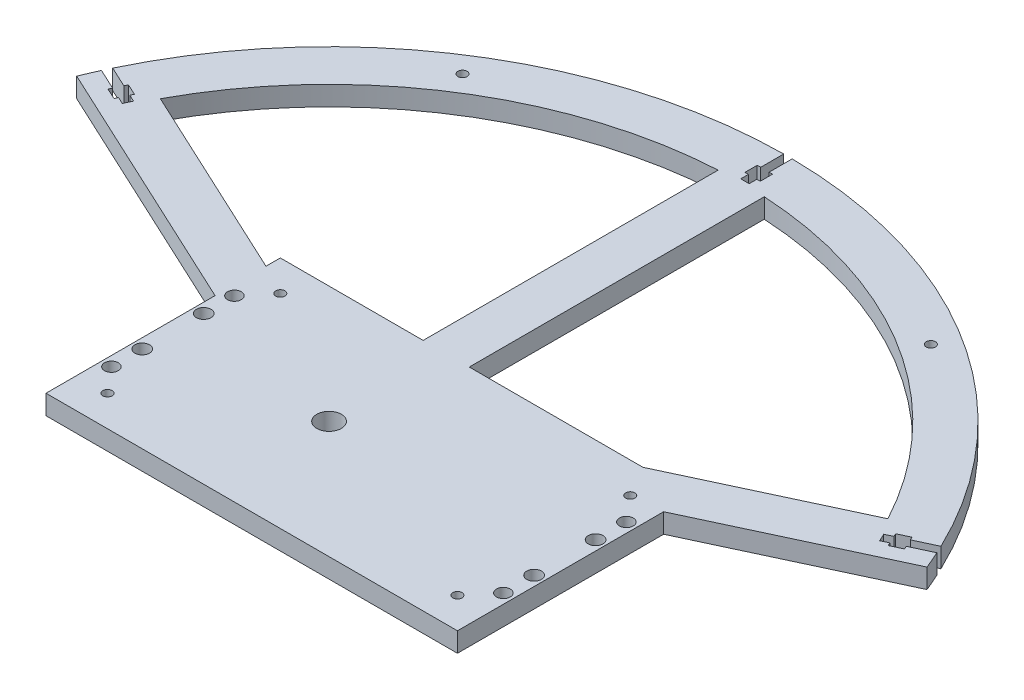
SolidWorks part; units mm, degrees
material "6061 Alloy"
ref_plane "Front Plane" through (0, 0, 0) normal (0, 0, 1) x (1, 0, 0)
ref_plane "Top Plane" through (0, 0, 0) normal (0, 1, 0) x (1, 0, 0)
ref_plane "Right Plane" through (0, 0, 0) normal (1, 0, 0) x (0, 0, -1)
sketch "Sketch1" plane through (0, 0, 0) normal (0, 1, 0) x (1, 0, 0)
  line L0 (0, 0) -> (0, 149.238) construction
  line L1 (0, 0) -> (135.2556, 63.0707) construction
  line L2 (0, 0) -> (-135.2556, 63.0707) construction
  line L3 (3.1696, 6.7973) -> (-132.0859, 69.868)
  line L4 (7.5, 0) -> (7.5, 149.238)
  line L5 (3.1696, -6.7973) -> (138.4252, 56.2734)
  line L6 (-3.1696, -6.7973) -> (-138.4252, 56.2734)
  line L7 (-7.5, 0) -> (-7.5, 149.238)
  line L8 (-3.1696, 6.7973) -> (132.0859, 69.868)
  line L10 (-53.95, -38.1) -> (79.85, -38.1)
  line L11 (-53.95, -38.1) -> (-53.95, 38.1)
  line L12 (-53.95, 38.1) -> (79.85, 38.1)
  line L13 (79.85, -38.1) -> (79.85, 38.1)
  line L14 (-53.95, -38.1) -> (79.85, 38.1) construction
  line L15 (-53.95, 38.1) -> (79.85, -38.1) construction
  circle A0 centre (0, 0) radius 150 construction
  circle A1 centre (0, 0) radius 149.238
  circle A2 centre (0, 0) radius 134.238
  circle A3 centre (0, 0) radius 14
  point P7 (0, 0)
  point P11 (0, 0)
  dimension "D1" = 150
  dimension "D2" = 0.762
  dimension "D3" = 15
  dimension "D10" = 28
  dimension "D4" = 65
  dimension "D5" = 65
  dimension "D8" = 133.8
  dimension "D9" = 76.2
  dimension "D11" = 53.95
  dimension "D12" = 38.1
  dimension "D6" = 7.5
  dimension "D7" = 7.5
extrude "Boss-Extrude1" add sketch "Sketch1" along normal mid plane 6.35
sketch "Sketch2" plane through (0, 0, 0) normal (0, 1, 0) x (1, 0, 0)
  line L0 (-1.375, 135.238) -> (-1.375, 149.238)
  line L1 (-1.375, 135.238) -> (1.375, 135.238)
  line L2 (-1.375, 149.238) -> (1.375, 149.238)
  line L3 (1.375, 135.238) -> (1.375, 149.238)
  line L4 (-1.375, 135.238) -> (1.375, 149.238) construction
  line L5 (-1.375, 149.238) -> (1.375, 135.238) construction
  line L6 (-2.5, 137.738) -> (-2.5, 141.738)
  line L7 (-2.5, 137.738) -> (2.5, 137.738)
  line L8 (-2.5, 141.738) -> (2.5, 141.738)
  line L9 (2.5, 137.738) -> (2.5, 141.738)
  line L10 (-2.5, 137.738) -> (2.5, 141.738) construction
  line L11 (-2.5, 141.738) -> (2.5, 137.738) construction
  line L12 (0, -1000) -> (0, 49000) construction
  line L13 (-1000, 0) -> (49000, 0) construction
  arc A1 (138.2543, 56.1937) -> (-138.2543, 56.1937) centre (0, 0) ccw construction
  point P1 (0, 142.238)
  point P2 (0, 139.738)
  dimension "D1" = 2.75
  dimension "D2" = 14
  dimension "D3" = 4
  dimension "D4" = 5
  dimension "D5" = 2.5
extrude "Cut-Extrude1" cut sketch "Sketch2" against normal through all both and the other way through all contours L7 L0 L1 L3 | L8 L0 L7 L3 | L7 L9 L8 L3 | L0 L8 L3 L2 | L8 L6 L7 L0
pattern_circular "CirPattern1" count 2 every 65 about axis through (0, 0, 0) along (0, 1, 0) of "Cut-Extrude1"
hole_wizard "Ø3.0 (3) Diameter Hole1" positions "Sketch3" profile "Sketch4" hole size "Ø3.0" standard "ANSI Metric" end condition up to next
sketch "Sketch3" plane through (0, 3.175, 0) normal (0, 1, 0) x (1, 0, 0)
  line L11 (0, 0) -> (-80.1855, 125.8661) construction
  line L13 (0, 0) -> (80.1855, 125.8661) construction
  line L16 (-43.95, -28.1) -> (69.85, -28.1)
  line L17 (-43.95, -28.1) -> (-43.95, 28.1)
  line L18 (-43.95, 28.1) -> (69.85, 28.1)
  line L19 (69.85, -28.1) -> (69.85, 28.1)
  line L20 (-43.95, -28.1) -> (69.85, 28.1) construction
  line L21 (-43.95, 28.1) -> (69.85, -28.1) construction
  line L24 (80.1855, 125.8661) -> (72.126, 113.2152)
  line L26 (-80.1855, 125.8661) -> (-72.126, 113.2152)
  line L32 (79.85, -38.1) -> (79.85, 28.9593) construction
  line L33 (-53.95, -38.1) -> (79.85, -38.1) construction
  line L34 (-53.95, -38.1) -> (-53.95, 16.882) construction
  line L35 (-53.95, 38.1) -> (-7.5, 38.1) construction
  arc A14 (-1.375, 149.2317) -> (-134.6687, 64.3142) centre (0, 0) ccw construction
  arc A15 (-7.5, 134.0283) -> (-118.3013, 63.4401) centre (0, 0) ccw construction
  arc A16 (134.6687, 64.3142) -> (1.375, 149.2317) centre (0, 0) ccw construction
  arc A17 (118.3013, 63.4401) -> (7.5, 134.0283) centre (0, 0) ccw construction
  point P107 (0, 0)
  point P324 (0, 0)
  point P605 (-76.1558, 119.5406)
  point P607 (76.1558, 119.5406)
  point P611 (69.85, 28.1)
  point P614 (69.85, -28.1)
  point P617 (-43.95, -28.1)
  point P620 (-43.95, 28.1)
  dimension "D1" = 10
  dimension "D2" = 10
  dimension "D3" = 10
  dimension "D4" = 10
sketch "Sketch4" plane through (0, 3.175, 0) normal (1, 0, 0) x (0, 0, 1)
  line L0 (0, 0) -> (0, 6.35)
  line L1 (0, 6.35) -> (1.5, 6.35)
  line L2 (1.5, 6.35) -> (1.5, 0)
  line L5 (1.5, 0) -> (0, 0)
  line L11 (0, -6.35) -> (0, 107.95) construction
  dimension "Thru Hole Dia." = 3
  dimension "Thru Hole Depth" = 6.35
hole_wizard "Ø8.0 (8) Diameter Hole1" positions "Sketch5" profile "Sketch6" hole size "Ø8.0" standard "ANSI Metric" end condition up to next
sketch "Sketch5" plane through (0, 3.175, 0) normal (0, 1, 0) x (1, 0, 0)
  point P0 (0, 0)
sketch "Sketch6" plane through (0, 3.175, 0) normal (1, 0, 0) x (0, 0, 1)
  line L0 (0, 0) -> (0, 6.35)
  line L1 (0, 6.35) -> (4, 6.35)
  line L2 (4, 6.35) -> (4, 0)
  line L5 (4, 0) -> (0, 0)
  line L11 (0, -6.35) -> (0, 107.95) construction
  dimension "Thru Hole Dia." = 8
  dimension "Thru Hole Depth" = 6.35
sketch "Sketch8" plane through (0, 3.175, 0) normal (0, 1, 0) x (1, 0, 0)
  line L0 (-47.6, 30) -> (-47.6, -30) construction
  line L1 (-47.6, -30) -> (-53.95, -30) construction
  line L2 (-53.95, -30) -> (-53.95, 30) construction
  line L3 (-53.95, 30) -> (-47.6, 30) construction
  line L4 (79.85, 30) -> (79.85, -30) construction
  line L6 (73.5, -30) -> (73.5, 30) construction
  line L8 (-47.6, 30) -> (-47.6, -30)
  line L9 (-47.6, -30) -> (-53.95, -30)
  line L10 (-53.95, -30) -> (-53.95, 30)
  line L11 (-53.95, 30) -> (-47.6, 30)
  line L12 (79.85, 30) -> (79.85, -30)
  line L13 (79.85, -30) -> (73.5, -30)
  line L14 (73.5, -30) -> (73.5, 30)
  line L15 (73.5, 30) -> (79.85, 30)
  circle A1 centre (76.675, 20) radius 1.7272
  circle A2 centre (76.675, 20) radius 1.7272
  circle A3 centre (76.675, -20) radius 1.7272
  circle A4 centre (76.675, -20) radius 1.7272
  circle A5 centre (76.675, -10) radius 2.3813
  circle A6 centre (76.675, -10) radius 2.3813
  circle A7 centre (76.675, 10) radius 2.3813
  circle A8 centre (76.675, 10) radius 2.3813
  circle A13 centre (-50.775, -20) radius 1.7272
  circle A15 centre (-50.775, -20) radius 1.7272
  circle A64 centre (-50.775, 20) radius 1.7272
  circle A65 centre (-50.775, 20) radius 1.7272
  circle A66 centre (-50.775, -10) radius 2.3812
  circle A67 centre (-50.775, -10) radius 2.3812
  circle A68 centre (-50.775, 10) radius 2.3812
  circle A69 centre (-50.775, 10) radius 2.3812
  dimension "D1" = 0
  dimension "D2" = 0
  dimension "D3" = 0
  dimension "D4" = 0
  dimension "D5" = 0
  dimension "D6" = 0
  dimension "D7" = 0
  dimension "D8" = 0
hole_wizard "#8 Clearance Hole1" positions "Sketch9" profile "Sketch10" hole size "#8" standard "ANSI Inch"
sketch "Sketch9" plane through (0, 3.175, 0) normal (0, 1, 0) x (1, 0, 0)
  point P0 (-50.775, -20)
  point P3 (-50.775, 20)
  point P6 (76.675, -20)
  point P9 (76.675, 20)
  point P13 (0, 0)
  point P14 (0, 0)
  point P15 (0, 0)
  point P16 (-50.775, -20)
  point P18 (-50.775, 20)
sketch "Sketch10" plane through (-50.775, 3.175, 20) normal (1, 0, 0) x (0, 0, 1)
  line L0 (0, 0) -> (0, 14.1807)
  line L1 (0, 14.1807) -> (2.2479, 12.83)
  line L2 (2.2479, 12.83) -> (2.2479, 0)
  line L5 (2.2479, 0) -> (0, 0)
  line L10 (0, 14.1807) -> (-2.2479, 12.83) construction
  line L11 (0, -6.35) -> (0, 107.95) construction
  dimension "Hole Dia." = 4.4958
  dimension "Hole Depth" = 12.83
  dimension "Drill Angle" = 118
hole_wizard "3/16 (0.1875) Dowel Hole1" positions "Sketch11" profile "Sketch12" hole size "3/16" standard "ANSI Inch"
sketch "Sketch11" plane through (0, 3.175, 0) normal (0, 1, 0) x (1, 0, 0)
  point P0 (-50.775, -10)
  point P3 (-50.775, 10)
  point P6 (76.675, -10)
  point P9 (76.675, 10)
  point P13 (0, 0)
  point P14 (0, 0)
  point P15 (-50.775, -10)
  point P17 (-50.775, 10)
sketch "Sketch12" plane through (-50.775, 3.175, 10) normal (1, 0, 0) x (0, 0, 1)
  line L0 (0, 0) -> (0, 14.2608)
  line L1 (0, 14.2608) -> (2.3812, 12.83)
  line L2 (2.3812, 12.83) -> (2.3812, 0)
  line L5 (2.3812, 0) -> (0, 0)
  line L10 (0, 14.2608) -> (-2.3813, 12.83) construction
  line L11 (0, -6.35) -> (0, 107.95) construction
  dimension "Hole Dia." = 4.7625
  dimension "Hole Depth" = 12.83
  dimension "Drill Angle" = 118
